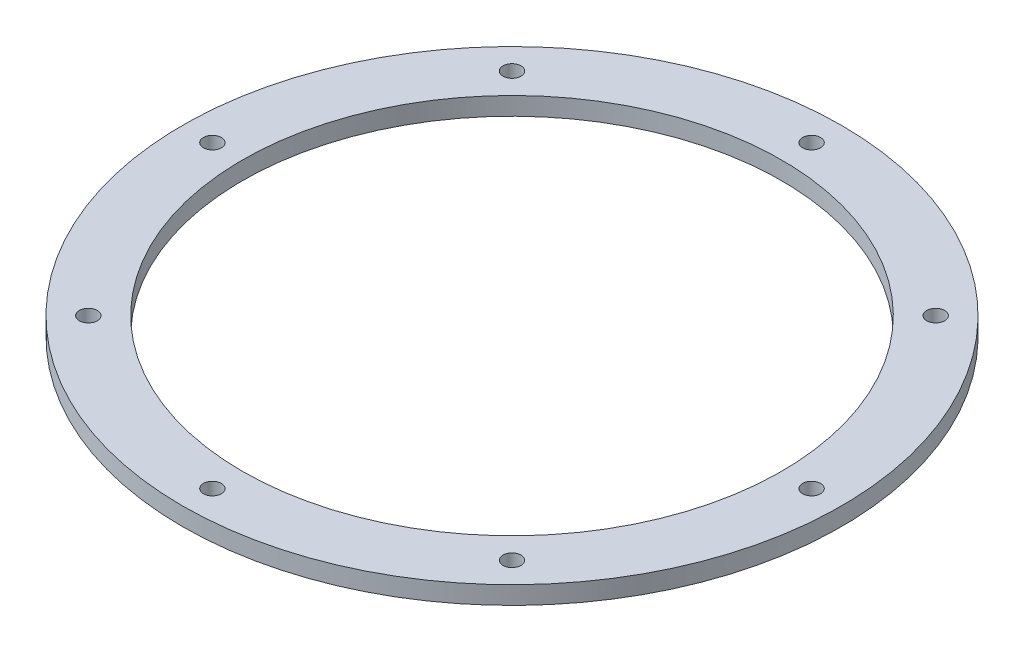
SolidWorks part; units mm, degrees
ref_plane "Front Plane" through (0, 0, 0) normal (0, 0, 1) x (1, 0, 0)
ref_plane "Top Plane" through (0, 0, 0) normal (0, 1, 0) x (1, 0, 0)
ref_plane "Right Plane" through (0, 0, 0) normal (1, 0, 0) x (0, 0, -1)
sketch "Sketch1" plane through (0, 0, 0) normal (0, 1, 0) x (1, 0, 0)
  circle A0 centre (0, 0) radius 55
  circle A1 centre (0, 0) radius 45
  dimension "D1" = 110
  dimension "D2" = 90
extrude "Boss-Extrude1" add sketch "Sketch1" along normal blind 3 contours A1 | A0
sketch "Sketch3" plane through (0, 3, 0) normal (0, 1, 0) x (1, 0, 0)
  circle A0 centre (0, 50) radius 1.5
  circle A1 centre (0, 0) radius 55 construction
  point P4 (0, 0)
  dimension "D2" = 3
  dimension "D1" = 50
extrude "Cut-Extrude1" cut sketch "Sketch3" against normal blind 3
pattern_curve "CrvPattern1" of "Cut-Extrude1" parameters "D1"=8, "D3"=50, "D2"=1, "D4"=50
